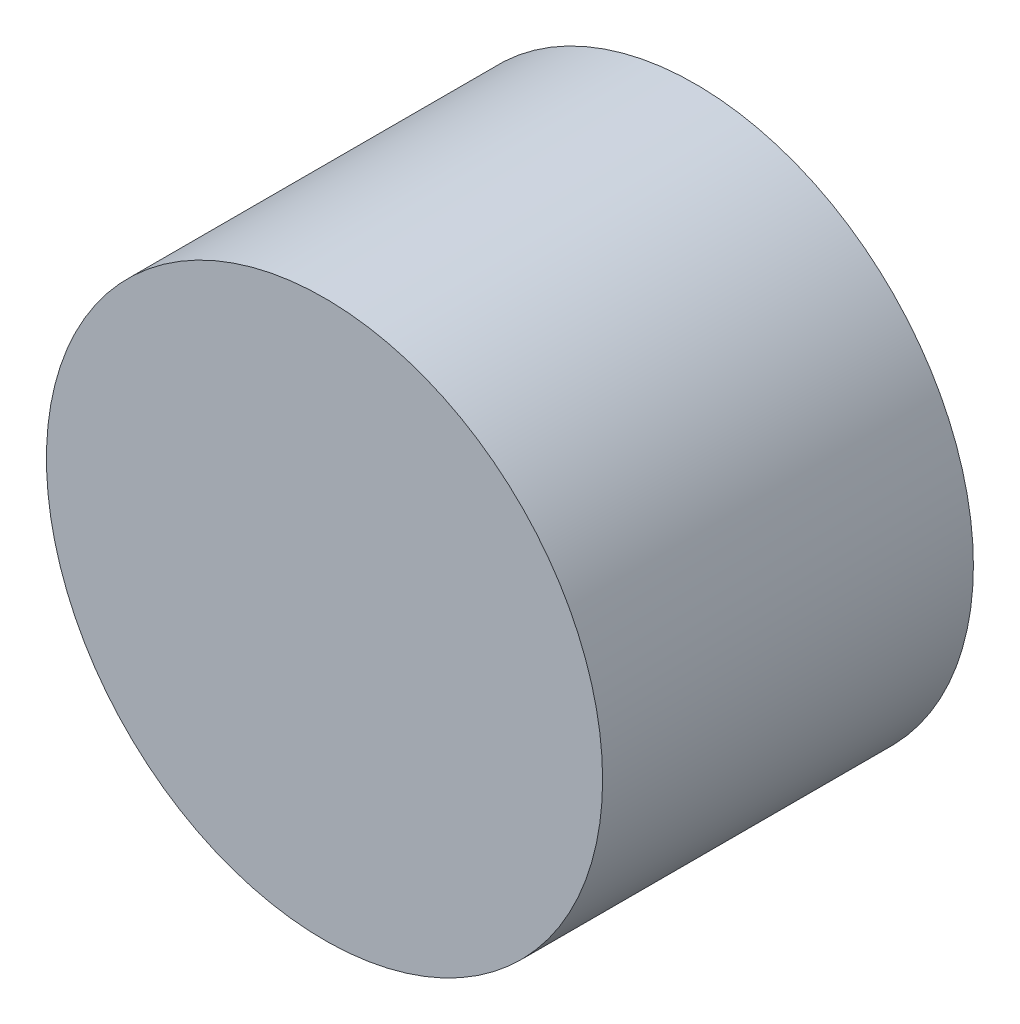
SolidWorks part; units mm, degrees
material "Nylon 6/10"
ref_plane "Front Plane" through (0, 0, 0) normal (0, 0, 1) x (1, 0, 0)
ref_plane "Top Plane" through (0, 0, 0) normal (0, 1, 0) x (1, 0, 0)
ref_plane "Right Plane" through (0, 0, 0) normal (1, 0, 0) x (0, 0, -1)
sketch "Sketch1" plane through (0, 0, 0) normal (0, 0, 1) x (1, 0, 0)
  circle A0 centre (0, 0) radius 4.7625
  dimension "D1" = 9.525
extrude "Extrude1" add sketch "Sketch1" along normal blind 6.35
